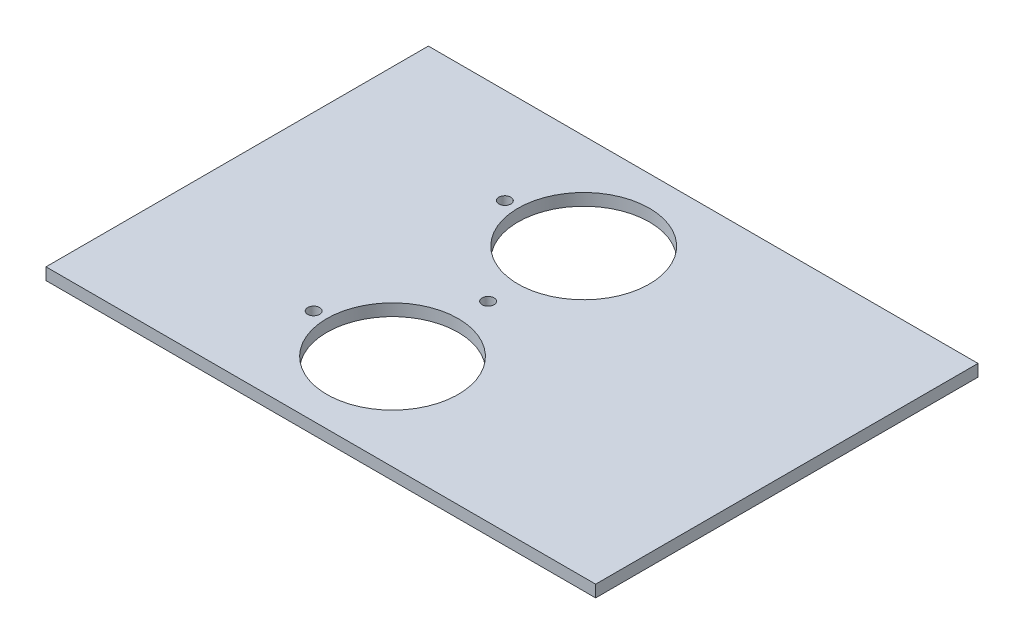
SolidWorks part; units mm, degrees
ref_plane "前视基准面" through (0, 0, 0) normal (0, 0, 1) x (1, 0, 0)
ref_plane "上视基准面" through (0, 0, 0) normal (0, 1, 0) x (1, 0, 0)
ref_plane "右视基准面" through (0, 0, 0) normal (1, 0, 0) x (0, 0, -1)
other "Configuration Table"
sketch "草图1" plane through (0, 0, 0) normal (0, 1, 0) x (1, 0, 0)
  line L1 (-125, -80) -> (125, -80)
  line L2 (-125, -80) -> (-125, 80)
  line L3 (-125, 80) -> (125, 80)
  line L4 (125, -80) -> (125, 80)
  line L5 (-125, -80) -> (125, 80) construction
  line L6 (-125, 80) -> (125, -80) construction
  point P0 (0, 0)
  dimension "D1" = 250
  dimension "D2" = 160
extrude "凸台-拉伸1" add sketch "草图1" along normal blind 5
sketch "草图2" plane through (0, 0, 0) normal (0, -1, 0) x (1, 0, 0)
  line L0 (-33, -40) -> (0, -40) construction
  line L1 (42.8083, 0) -> (0, 0) construction
  line L2 (0, 0) -> (0, -40) construction
  line L3 (-125, -80) -> (-125, 80) construction
  line L4 (-145, -80) -> (-105, -80)
  line L5 (-145, -80) -> (-145, 80)
  line L6 (-145, 80) -> (-105, 80)
  line L7 (-105, -80) -> (-105, 80)
  line L8 (-145, -80) -> (-105, 80) construction
  line L9 (-145, 80) -> (-105, -80) construction
  line L10 (125, -80) -> (-125, -80) construction
  circle A0 centre (0, -40) radius 27.5
  circle A1 centre (0, -40) radius 33 construction
  circle A2 centre (-33, -40) radius 2.5
  circle A3 centre (-33, 40) radius 2.5
  circle A4 centre (0, 40) radius 27.5
  circle A5 centre (0, 0) radius 2.5
  point P2 (-125, 0)
  dimension "D1" = 55
  dimension "D2" = 66
  dimension "D3" = 5
  dimension "D6" = 5
  dimension "D4" = 40
  dimension "D5" = 20
extrude "切除-拉伸1" cut sketch "草图2" against normal up to next
